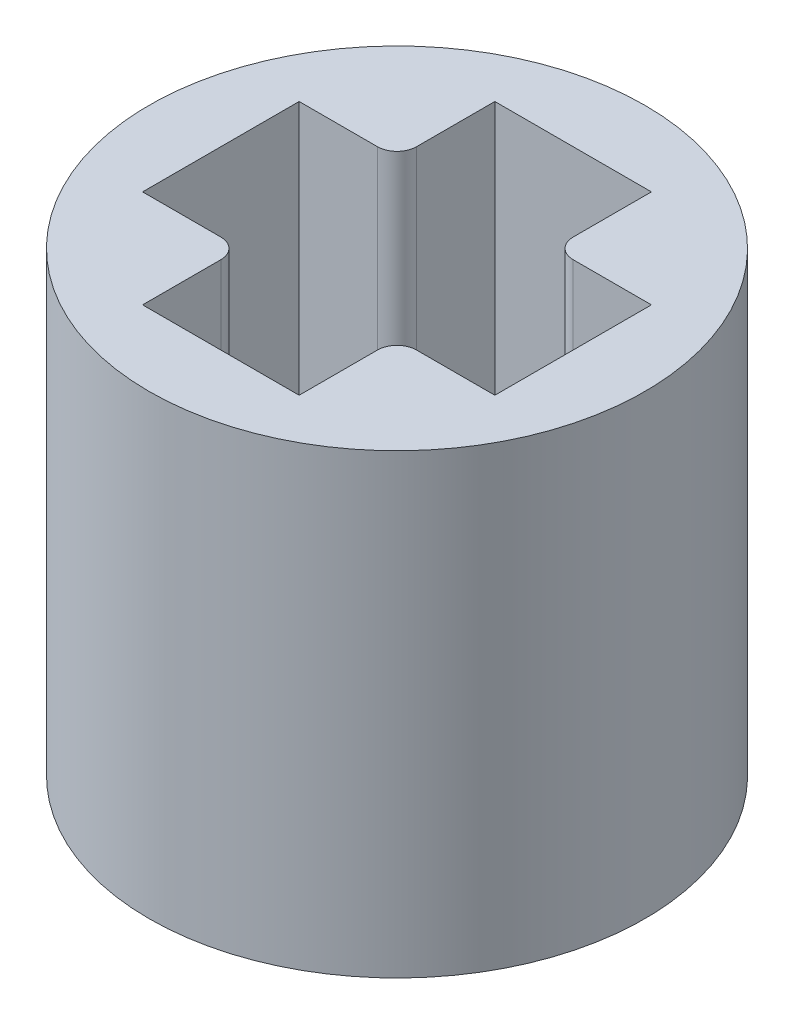
SolidWorks part; units mm, degrees
ref_plane "Front Plane" through (0, 0, 0) normal (0, 0, 1) x (1, 0, 0)
ref_plane "Top Plane" through (0, 0, 0) normal (0, 1, 0) x (1, 0, 0)
ref_plane "Right Plane" through (0, 0, 0) normal (1, 0, 0) x (0, 0, -1)
sketch "Sketch1" plane through (0, 0, 0) normal (0, 1, 0) x (1, 0, 0)
  line L14 (1.5, -1.2) -> (2.7, -1.2)
  line L15 (2.7, -1.2) -> (2.7, 1.2)
  line L16 (1.5, 1.2) -> (2.7, 1.2)
  line L17 (1.2, 2.7) -> (1.2, 1.5)
  line L18 (-1.2, 2.7) -> (1.2, 2.7)
  line L19 (-1.2, 2.7) -> (-1.2, 1.5)
  line L20 (-1.5, 1.2) -> (-2.7, 1.2)
  line L21 (-2.7, -1.2) -> (-2.7, 1.2)
  line L22 (-1.5, -1.2) -> (-2.7, -1.2)
  line L23 (-1.2, -2.7) -> (-1.2, -1.5)
  line L24 (-1.2, -2.7) -> (1.2, -2.7)
  line L25 (1.2, -2.7) -> (1.2, -1.5)
  circle A5 centre (0, 0) radius 3.8
  arc A6 (1.2, -1.5) -> (1.5, -1.2) centre (1.5, -1.5) cw
  arc A7 (1.5, 1.2) -> (1.2, 1.5) centre (1.5, 1.5) cw
  arc A8 (-1.2, 1.5) -> (-1.5, 1.2) centre (-1.5, 1.5) cw
  arc A9 (-1.5, -1.2) -> (-1.2, -1.5) centre (-1.5, -1.5) cw
  point P13 (0, -2.5)
extrude "Boss-Extrude1" add sketch "Sketch1" along normal blind 7
